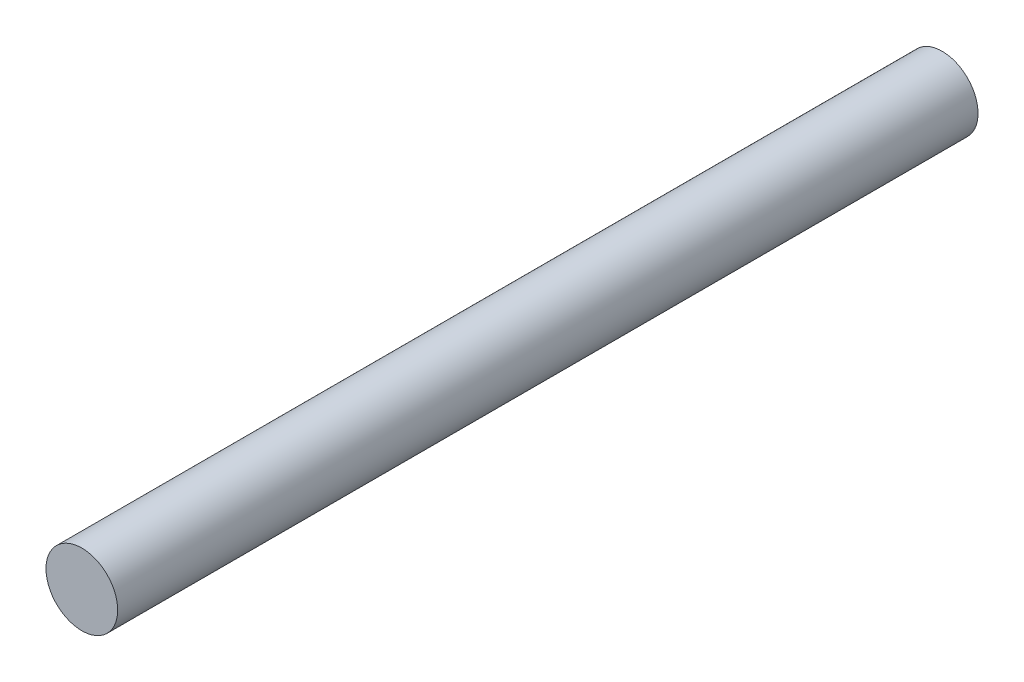
SolidWorks part; units mm, degrees
ref_plane "Front Plane" through (0, 0, 0) normal (0, 0, 1) x (1, 0, 0)
ref_plane "Top Plane" through (0, 0, 0) normal (0, 1, 0) x (1, 0, 0)
ref_plane "Right Plane" through (0, 0, 0) normal (1, 0, 0) x (0, 0, -1)
sketch "Sketch1" plane through (0, 0, 0) normal (0, 0, 1) x (1, 0, 0)
  circle A0 centre (0, 0) radius 6.35
  point P4 (0, 0)
  dimension "D1" = 12.7
extrude "Boss-Extrude1" add sketch "Sketch1" along normal blind 152.4
